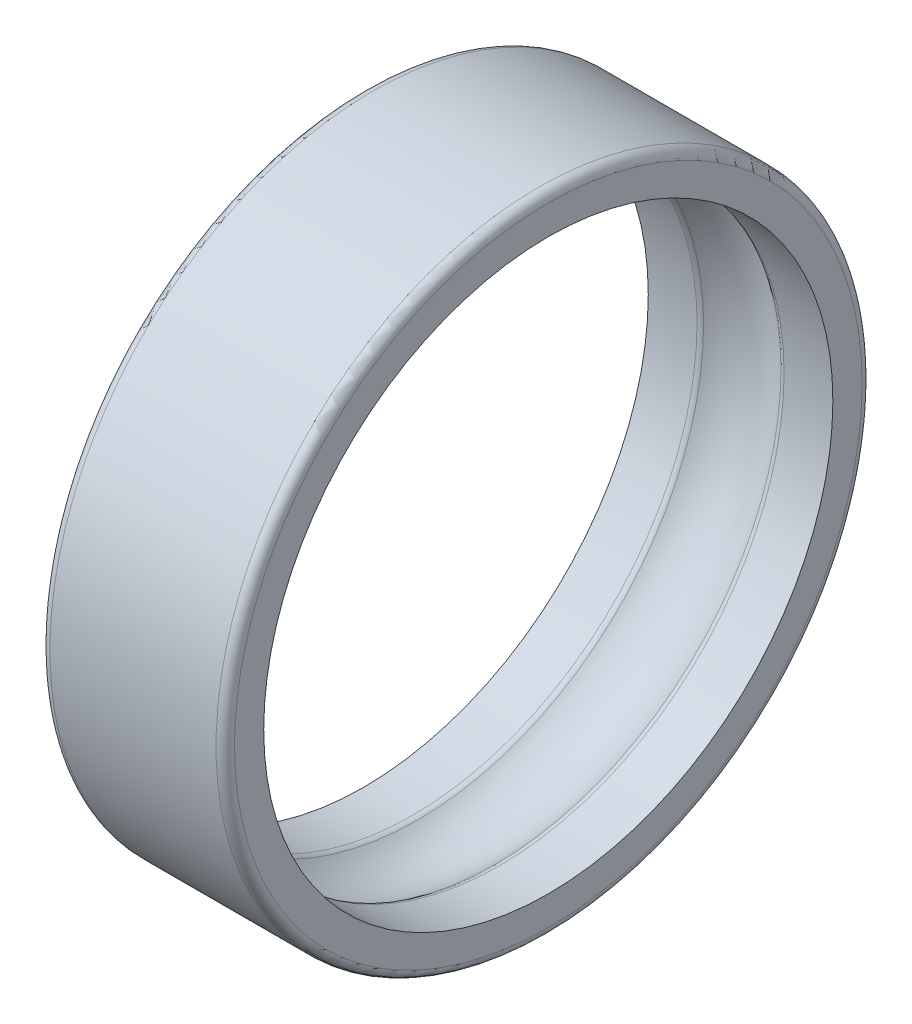
SolidWorks part; units mm, degrees
ref_plane "Front Plane" through (0, 0, 0) normal (0, 0, 1) x (1, 0, 0)
ref_plane "Top Plane" through (0, 0, 0) normal (0, 1, 0) x (1, 0, 0)
ref_plane "Right Plane" through (0, 0, 0) normal (1, 0, 0) x (0, 0, -1)
sketch "Sketch1" plane through (0, 0, 0) normal (0, 0, 1) x (1, 0, 0)
  line L0 (44.1264, -10.7992) -> (-44.1264, -10.7992) construction
  line L1 (44.1264, -10.7992) -> (-44.1264, -10.7992) construction
  line L3 (-6, 10.2008) -> (6, 10.2008)
  line L4 (-6, 10.2008) -> (-6, 7.7008)
  line L5 (-6, 7.7008) -> (6, 7.7008)
  line L6 (6, 10.2008) -> (6, 7.7008)
  line L7 (0, 8.7008) -> (0, 0.7008) construction
  circle A2 centre (0, 4.7008) radius 4
  point P9 (0, 7.7008)
  dimension "D3" = 8
  dimension "D1" = 12
  dimension "D2" = 42
  dimension "D4" = 3
  dimension "D5" = 5.5
revolve "Revolve1" add sketch "Sketch1" angle 360 about L1
fillet "Fillet2" radius 0.6 2 edges at (-6, 10.2008, 0) (6, 10.2008, 0)
fillet "Fillet3" radius 0.5 2 edges at (-2.6458, 7.7008, 0) (2.6458, 7.7008, 0)
equation "\"D2@Sketch1\"=\"d_ext_roulement_rouleau\""
equation "\"D1@Sketch1\"=\"B_roulement_rouleau\""
equation "\"r_roulement_rouleau\"= 0.6"
equation "\"d_ext_rouleau\"= 90"
equation "\"epaisseur_rouleau\"=80"
equation "\"alesage-rouleau\"= 52"
equation "\"jeu_dent_rouleau\"= 2"
equation "\"profondeur_dent_rouleau\"=4"
equation "\"n_dent_roueau\"= 15"
equation "\"d_ext_roulement_rouleau\"= 42"
equation "\"d_int_roulement_rouleau\"= 20"
equation "\"B_roulement_rouleau\"= 12"
equation "\"d_bille_roulement_rouleau\"= 8"
equation "\"F_anneau_alesage_rouleau\"=1.85"
equation "\"G_anneau_alesage_rouleau\"=47.5"
equation "\"K_anneau_alesage_rouleau\"=3.75"
equation "\"d_vis_flasque_rouleau\"=5"
equation "\"l-x_vis_flasque_rouleau\"=4"
equation "\"g_anneau_arbre_rouleau\"=19"
equation "\"f_anneau_arbre_rouleau\"=1.3"
equation "\"k_anneau_arbre_rouleau\"=1.5"
equation "\"h_matrice\"= 18"
equation "\"d_matrice\"= 220"
equation "\"d_granulat\"= 8"
equation "\"zone_vide_matrice\" = 48"
equation "\"d_alesage_matrice\"=20"
equation "\"a_clavette_alesage_matrice\"=6"
equation "\"entrax_vis_rouleau\"=65"
equation "\"D3@Sketch1\"=\"d_bille_roulement_rouleau\""
equation "\"D4@Sketch1\"=(\"d_bille_roulement_rouleau\"/2)-1"
equation "\"D5@Sketch1\"=(\"d_ext_roulement_rouleau\"-\"d_int_roulement_rouleau\")*0.25"
equation "\"D1@Fillet2\"=\"r_roulement_rouleau\""
